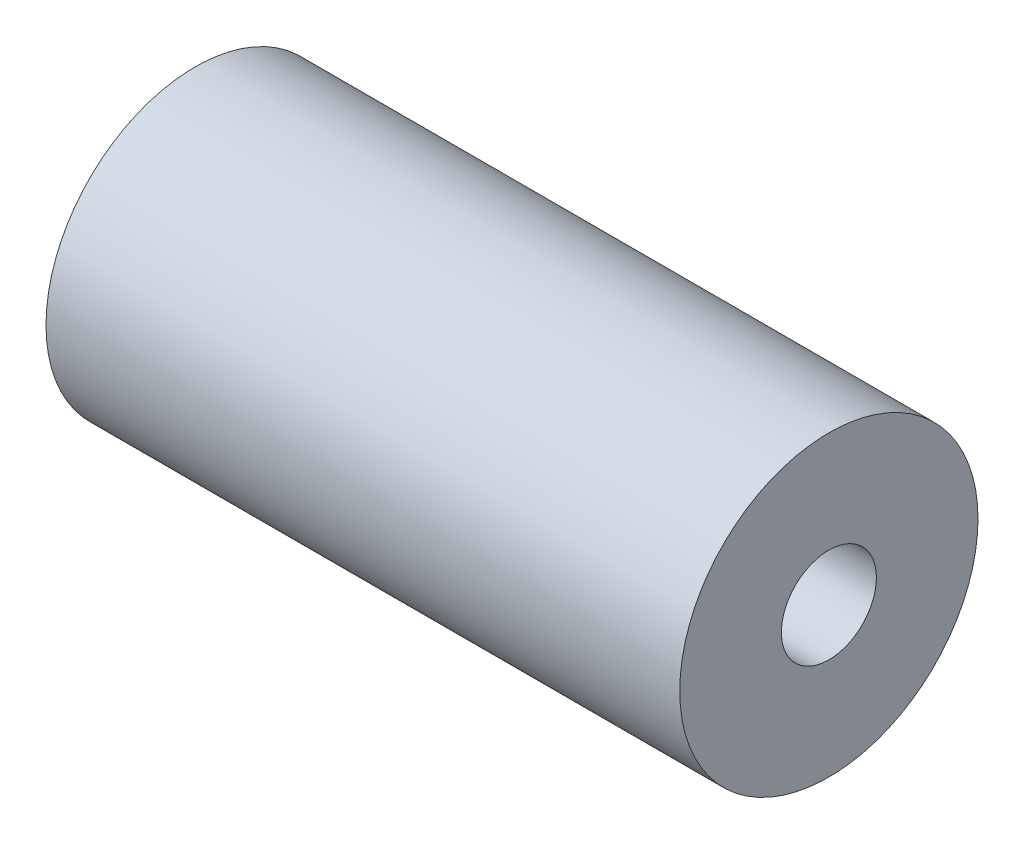
SolidWorks part; units mm, degrees
material "Delrin 2700 NC010, Low Viscosity Acetal Copolymer (SS)"
ref_plane "Front Plane" through (0, 0, 0) normal (0, 0, 1) x (1, 0, 0)
ref_plane "Top Plane" through (0, 0, 0) normal (0, 1, 0) x (1, 0, 0)
ref_plane "Right Plane" through (0, 0, 0) normal (1, 0, 0) x (0, 0, -1)
sketch "Sketch1" plane through (0, 0, 0) normal (1, 0, 0) x (0, 0, -1)
  circle A0 centre (0, 0) radius 8
  circle A1 centre (0, 0) radius 2.55
  dimension "D1" = 16
  dimension "D2" = 5.1
extrude "Boss-Extrude1" add sketch "Sketch1" along normal blind 34
